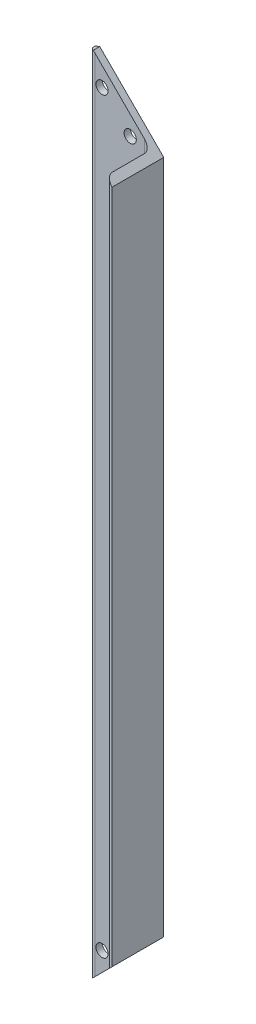
SolidWorks part; units mm, degrees
material "Plain Carbon Steel"
ref_plane "Front Plane" through (0, 0, 0) normal (0, 0, 1) x (1, 0, 0)
ref_plane "Top Plane" through (0, 0, 0) normal (0, 1, 0) x (1, 0, 0)
ref_plane "Right Plane" through (0, 0, 0) normal (1, 0, 0) x (0, 0, -1)
sketch "Sketch1" plane through (0, 0, 0) normal (0, 0, 1) x (1, 0, 0)
  line L0 (0, 300) -> (0, -300)
  dimension "D1" = 600
other "L angle L2X1.5X0.1875(1)"
ref_plane "Plane1" through (0, 300, 0) normal (0, -1, 0) x (0, 0, 1)
sketch "Sketch14" plane through (0, 300, 0) normal (0, -1, 0) x (0, 0, 1)
  line L0 (0, 0) -> (0, 50.8)
  line L1 (0, 50.8) -> (0.0051, 50.8)
  line L2 (4.7625, 46.0426) -> (4.7625, 9.525)
  line L3 (9.525, 4.7625) -> (33.3426, 4.7625)
  line L4 (38.1, 0.0051) -> (38.1, 0)
  line L5 (38.1, 0) -> (0, 0)
  arc A0 (38.1, 0.0051) -> (33.3426, 4.7625) centre (33.3426, 0.0051) ccw
  arc A1 (0.0051, 50.8) -> (4.7625, 46.0426) centre (0.0051, 46.0426) cw
  arc A2 (9.525, 4.7625) -> (4.7625, 9.525) centre (9.525, 9.525) cw
  circle A3 centre (0, 0) radius 4.7625 construction
  point P10 (0, 25.4)
  point P14 (19.05, 0)
  point P15 (0, 0)
  dimension "D2" = 0.0051
  dimension "Radius_1" = 4.7625
  dimension "Radius_2" = 4.7625
  dimension "D1" = 4.7625
  dimension "V_leg" = 50.8
  dimension "H_leg" = 38.1
  dimension "Thickness" = 4.7625
  dimension "Flat_wid" = 0.0051
sketch "Sketch15" plane through (0, 0, 0) normal (0, 0, 1) x (1, 0, 0)
  line L0 (-50.8, 300) -> (-47.2645, 296.4645) construction
  line L7 (-50.8, -300) -> (0, -300)
  line L8 (-50.8, 300) -> (0, 300)
  line L9 (0, 300) -> (0, 249.2)
  line L10 (-50.8, 300) -> (-50.8, 295)
  line L11 (-47.2645, 296.4645) -> (0, 249.2)
  line L12 (-50.8, 295) -> (-47.2645, 296.4645)
  line L14 (0, -300) -> (0, -249.2)
  line L15 (0, -249.2) -> (-48.3, -297.5)
  line L17 (-50.8, -300) -> (-46.0426, -300) construction
  line L18 (-48.3, -297.5) -> (-50.8, -295)
  line L19 (-50.8, -300) -> (-50.8, 300) construction
  line L20 (-50.8, -295) -> (-50.8, -300)
  line L21 (-50.8, -300) -> (-48.3, -297.5) construction
  point P3 (-0.0051, -201.216)
  dimension "D1" = 5
  dimension "D2" = 5
  dimension "D3" = 45
  dimension "D4" = 45
extrude "Cut-Extrude1" cut sketch "Sketch15" along normal up to next
hole_wizard "M8 Clearance Hole1" positions "Sketch17" profile "Sketch18" hole size "M8" standard "ANSI Metric" end condition up to next
sketch "Sketch17" plane through (0, 0, 4.7625) normal (0, 0, 1) x (1, 0, 0)
  line L4 (-40.8, 275.8579) -> (-40.8, 255.0629)
  line L5 (-40.8, 255.0629) -> (-20.0051, 255.0629)
  line L9 (-40.8, 275.8579) -> (-20.0051, 255.0629)
  line L19 (-20.0051, -255.0629) -> (-40.8, -275.8579)
  line L21 (-46.0426, -295.2426) -> (-9.525, -258.725) construction
  line L22 (-9.525, 258.725) -> (-46.0426, 295.2426) construction
  line L26 (-50.8, -295) -> (-50.8, 295) construction
  line L27 (-0.0051, -249.2051) -> (-0.0051, 249.2051) construction
  line L28 (-40.8, -275.8579) -> (-40.8, -255.0629)
  line L29 (-40.8, -255.0629) -> (-20.0051, -255.0629)
  line L31 (-20.0051, 255.0629) -> (-20.0051, -255.0629)
  point P0 (-40.8, 275.8579)
  point P2 (-20.0051, 255.0629)
  point P6 (-20.0051, -255.0629)
  point P63 (-40.8, -275.8579)
  dimension "D1" = 10
  dimension "D2" = 10
  dimension "D3" = 10
  dimension "D5" = 20
sketch "Sketch18" plane through (-40.8, 275.8579, 4.7625) normal (1, 0, 0) x (0, -1, 0)
  line L0 (0, 0) -> (0, 4.7625)
  line L1 (0, 4.7625) -> (4.5, 4.7625)
  line L2 (4.5, 4.7625) -> (4.5, 0)
  line L5 (4.5, 0) -> (0, 0)
  line L11 (0, -6.35) -> (0, 107.95) construction
  dimension "Thru Hole Dia." = 9
  dimension "Thru Hole Depth" = 4.7625
